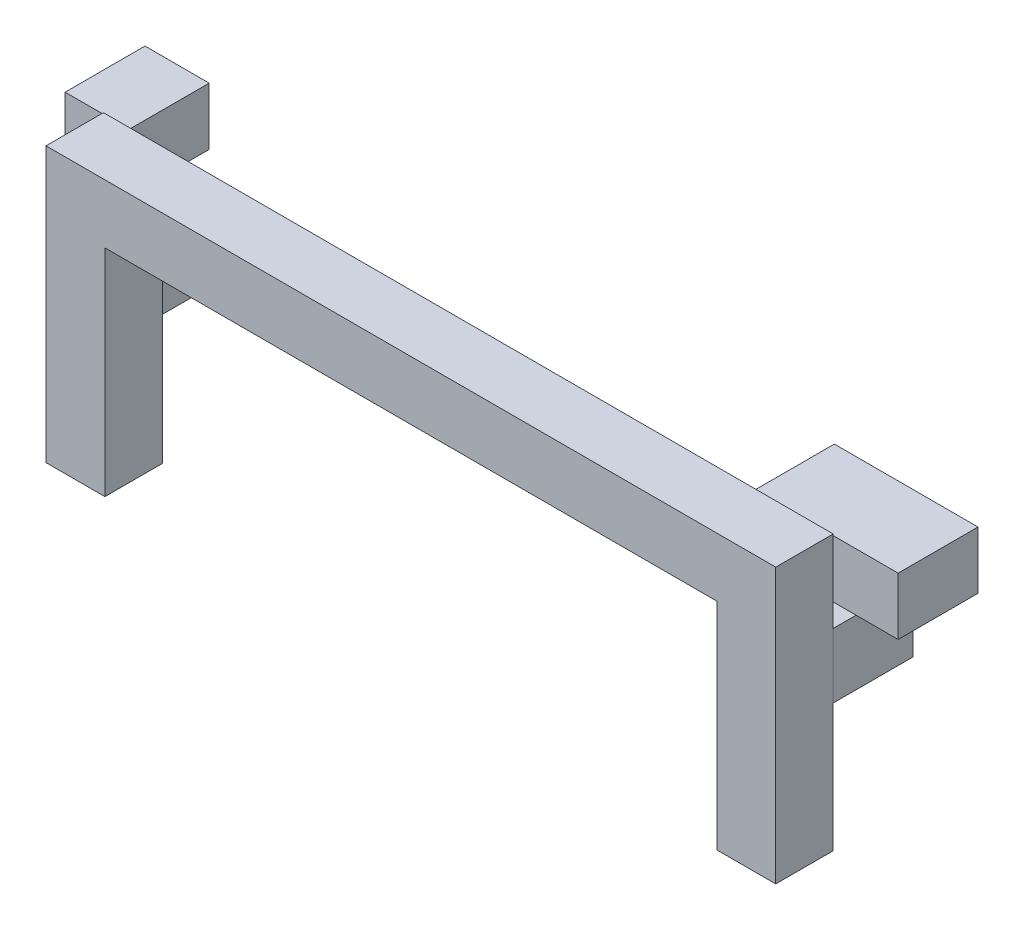
SolidWorks part; units mm, degrees
ref_plane "Front Plane" through (0, 0, 0) normal (0, 0, 1) x (1, 0, 0)
ref_plane "Top Plane" through (0, 0, 0) normal (0, 1, 0) x (1, 0, 0)
ref_plane "Right Plane" through (0, 0, 0) normal (1, 0, 0) x (0, 0, -1)
sketch "Sketch2" plane through (0, 0, 0) normal (0, 0, 1) x (1, 0, 0)
  line L0 (-114.7456, -10.0965) -> (-114.7456, -148.4892)
  line L1 (-368.7456, -10.0965) -> (139.2544, -10.0965)
  line L2 (-368.7456, -10.0965) -> (-368.7456, -51.0965)
  line L3 (-368.7456, -51.0965) -> (139.2544, -51.0965)
  line L4 (139.2544, -10.0965) -> (139.2544, -51.0965)
  dimension "D1" = 41
  dimension "D2" = 508
extrude "Boss-Extrude1" add sketch "Sketch2" along normal blind 40 contours L2 L3 L0 L1 | L4 L1 L0 L3
sketch "Sketch3" plane through (0, 0, 0) normal (0, 0, -1) x (-1, 0, 0)
  line L1 (395.4356, -51.0965) -> (350.7456, -51.0965)
  line L2 (395.4356, -51.0965) -> (395.4356, -11.0965)
  line L3 (395.4356, -11.0965) -> (350.7456, -11.0965)
  line L4 (350.7456, -51.0965) -> (350.7456, -11.0965)
  line L5 (368.7456, -51.0965) -> (-139.2544, -51.0965) construction
  line L6 (114.7456, -10.0965) -> (114.7456, -89.8517)
  line L7 (368.7456, -10.0965) -> (-139.2544, -10.0965) construction
  line L8 (-165.9444, -11.0965) -> (-121.2544, -11.0965)
  line L9 (-121.2544, -51.0965) -> (-121.2544, -11.0965)
  line L10 (-165.9444, -51.0965) -> (-121.2544, -51.0965)
  line L11 (-165.9444, -51.0965) -> (-165.9444, -11.0965)
  dimension "D1" = 40
  dimension "D2" = 44.69
  dimension "D3" = 236
  dimension "D4" = 0
extrude "Boss-Extrude6" add sketch "Sketch3" along normal blind 55.6 contours L4 L1 L2 L3
sketch "Sketch7" plane through (0, 0, 0) normal (0, 0, -1) x (-1, 0, 0)
  line L1 (350.7456, -51.0965) -> (350.7456, -11.0965) construction
  line L2 (-184.4644, -11.0965) -> (-84.4644, -11.0965)
  line L3 (-184.4644, -11.0965) -> (-184.4644, -51.0965)
  line L4 (-184.4644, -51.0965) -> (-84.4644, -51.0965)
  line L5 (-84.4644, -11.0965) -> (-84.4644, -51.0965)
  line L6 (350.7456, -51.0965) -> (-139.2544, -51.0965) construction
  dimension "D1" = 40
  dimension "D2" = 100
  dimension "D3" = 435.21
  dimension "D4" = 0
extrude "Boss-Extrude7" add sketch "Sketch7" along normal blind 55.6
sketch "Sketch8" plane through (0, -51.0965, 0) normal (0, -1, 0) x (1, 0, 0)
  line L0 (-368.7456, 40) -> (139.2544, 40) construction
  line L1 (139.2544, 0) -> (98.2544, 0)
  line L2 (139.2544, 0) -> (139.2544, 40)
  line L3 (139.2544, 40) -> (98.2544, 40)
  line L4 (98.2544, 0) -> (98.2544, 40)
  line L6 (-368.7456, 0) -> (-327.7456, 0)
  line L7 (-368.7456, 0) -> (-368.7456, 40)
  line L8 (-368.7456, 40) -> (-327.7456, 40)
  line L9 (-327.7456, 0) -> (-327.7456, 40)
  dimension "D1" = 41
  dimension "D2" = 41
  dimension "D3" = 40
extrude "Boss-Extrude8" add sketch "Sketch8" along normal blind 150
sketch "Sketch9" plane through (0, 0, 0) normal (0, 0, -1) x (-1, 0, 0)
  line L0 (-139.2544, -10.0965) -> (-139.2544, -11.0965) construction
  line L1 (-139.1544, -67.1421) -> (-99.1544, -67.1421)
  line L2 (-139.1544, -67.1421) -> (-139.1544, -112.1421)
  line L3 (-139.1544, -112.1421) -> (-99.1544, -112.1421)
  line L4 (-99.1544, -67.1421) -> (-99.1544, -112.1421)
  line L5 (368.7456, -10.0965) -> (368.7456, -11.0965) construction
  line L6 (328.6456, -67.1421) -> (368.6456, -67.1421)
  line L7 (328.6456, -67.1421) -> (328.6456, -112.1421)
  line L8 (328.6456, -112.1421) -> (368.6456, -112.1421)
  line L9 (368.6456, -67.1421) -> (368.6456, -112.1421)
  line L10 (327.7456, -51.0965) -> (-84.4644, -51.0965) construction
  line L11 (368.7456, -51.0965) -> (350.7456, -51.0965) construction
  point P4 (-139.1544, -89.6421)
  point P17 (359.7456, -51.0965)
  dimension "D1" = 45
  dimension "D2" = 40
  dimension "D3" = 0.1
  dimension "D4" = 40
  dimension "D5" = 0.1
  dimension "D6" = 16.0456
  dimension "D7" = 16.0456
  dimension "D8" = 45
extrude "Boss-Extrude9" add sketch "Sketch9" along normal blind 55.6
